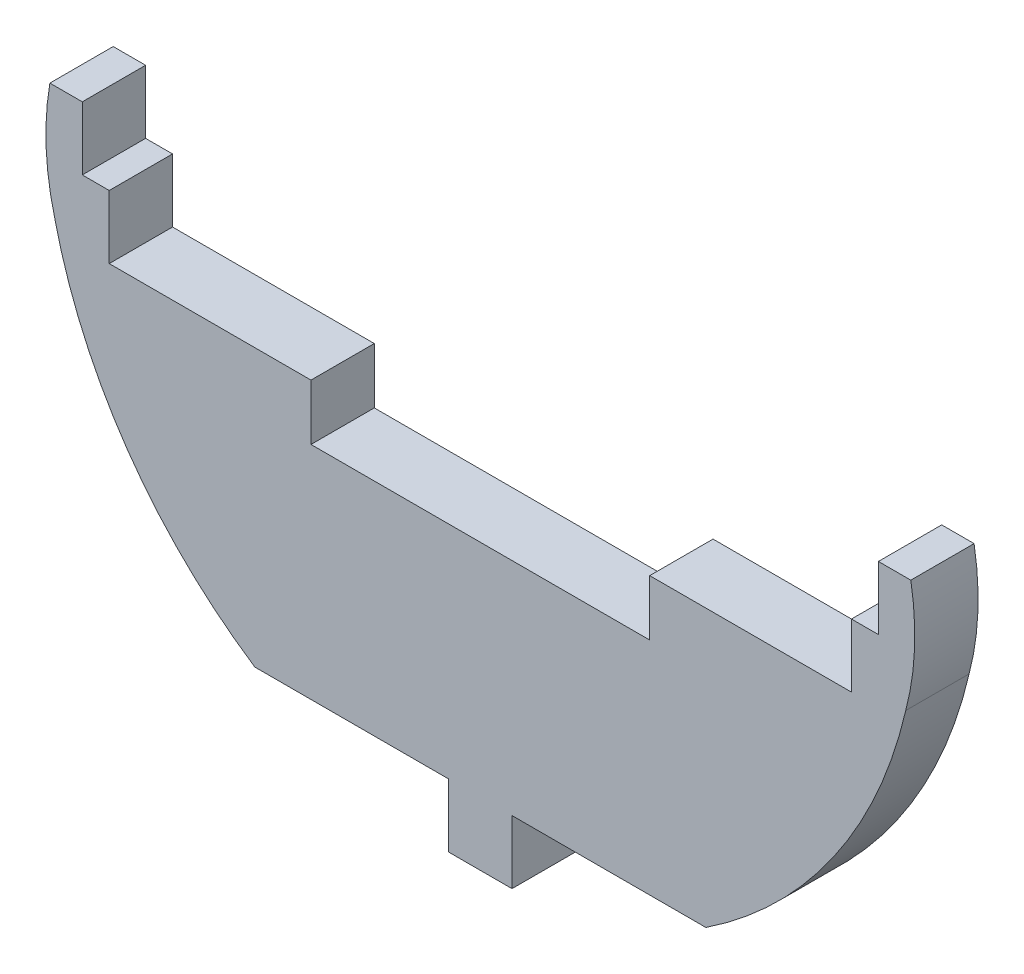
SolidWorks part; units mm, degrees
ref_plane "Front Plane" through (0, 0, 0) normal (0, 0, 1) x (1, 0, 0)
ref_plane "Top Plane" through (0, 0, 0) normal (0, 1, 0) x (1, 0, 0)
ref_plane "Right Plane" through (0, 0, 0) normal (1, 0, 0) x (0, 0, -1)
sketch "Sketch1" plane through (0, 0, 0) normal (0, 0, 1) x (1, 0, 0)
  line L0 (0, 0) -> (0, 13.464) construction
  line L1 (8.024, 13.464) -> (-8.024, 13.464)
  line L2 (-8.024, 13.464) -> (-8.024, 16.106)
  line L3 (-8.024, 16.106) -> (-17.583, 16.106)
  line L4 (-17.583, 16.106) -> (-17.583, 19.106)
  line L5 (-17.583, 19.106) -> (-18.859, 19.106)
  line L6 (-18.859, 19.106) -> (-18.859, 22.106)
  line L7 (1.5, 0) -> (-1.5, 0)
  line L8 (-1.5, 0) -> (-1.5, 3)
  line L9 (-1.5, 3) -> (-10.684, 3)
  line L10 (0, 13.464) -> (-19.105, 25.882) construction
  line L11 (0, 13.464) -> (-20.154, 16.635) construction
  line L12 (-18.859, 22.106) -> (-20.3945, 22.106)
  line L13 (1.5, 0) -> (1.5, 3)
  line L14 (1.5, 3) -> (10.684, 3)
  line L15 (18.859, 22.106) -> (20.3945, 22.106)
  line L16 (18.859, 19.106) -> (18.859, 22.106)
  line L17 (17.583, 19.106) -> (18.859, 19.106)
  line L18 (17.583, 16.106) -> (17.583, 19.106)
  line L19 (8.024, 16.106) -> (17.583, 16.106)
  line L20 (8.024, 13.464) -> (8.024, 16.106)
  arc A0 (-19.105, 25.882) -> (-20.154, 16.635) centre (-7.8154, 19.9183) ccw
  arc A1 (-20.154, 16.635) -> (-10.684, 3) centre (1.6939, 21.703) ccw
  arc A2 (20.154, 16.635) -> (10.684, 3) centre (-1.6939, 21.703) cw
  arc A3 (19.105, 25.882) -> (20.154, 16.635) centre (7.8154, 19.9183) cw
  point P31 (0, 0)
  dimension "D16" = 25.536
  dimension "D17" = 44.856
  dimension "D1" = 13.464
  dimension "D2" = 8.024
  dimension "D3" = 2.642
  dimension "D4" = 9.559
  dimension "D5" = 3
  dimension "D6" = 1.276
  dimension "D7" = 3
  dimension "D8" = 1.5
  dimension "D9" = 3
  dimension "D10" = 9.184
  dimension "D11" = 19.105
  dimension "D12" = 12.418
  dimension "D13" = 20.154
  dimension "D14" = 3.171
extrude "Boss-Extrude1" add sketch "Sketch1" along normal blind 3 contours A3 L15 L16 L17 L18 L19 L20 L1 L2 L3 L4 L5 L6 L12 A0 A1 L9 L8 L7 L13 L14 A2
